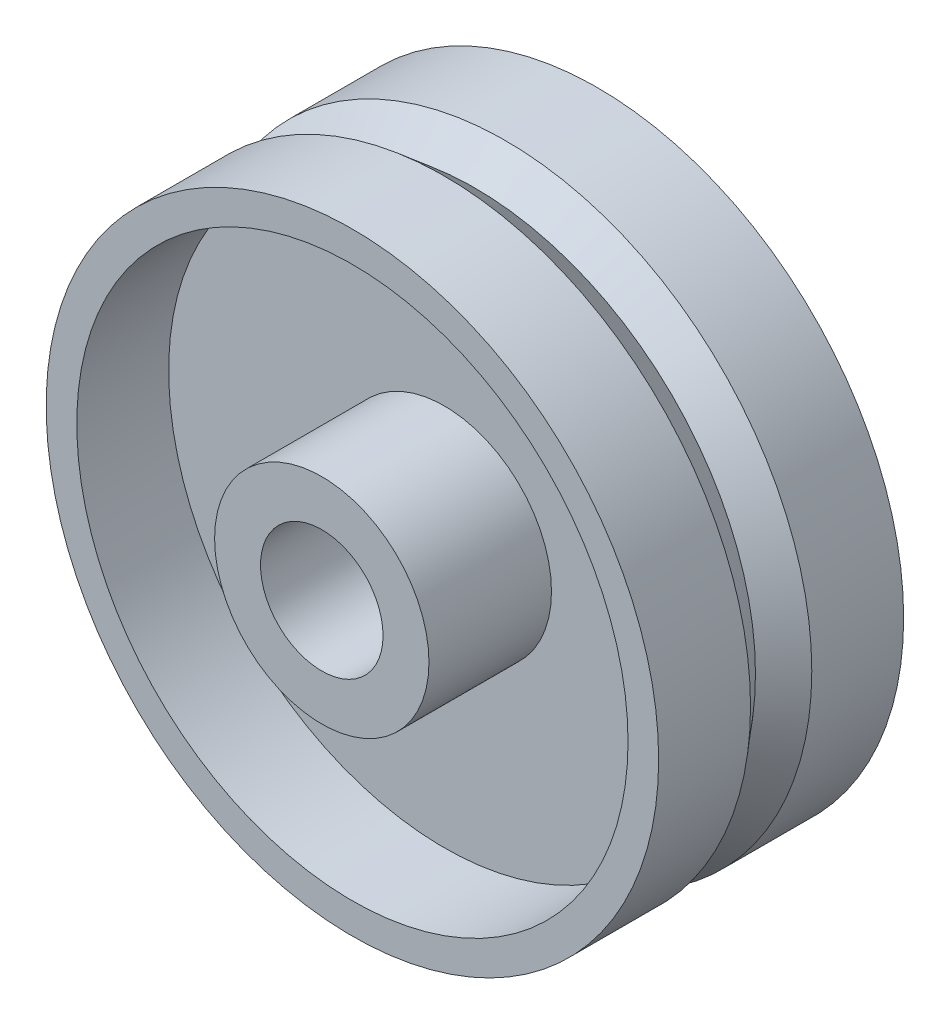
SolidWorks part; units mm, degrees
material "AISI 304"
ref_plane "Front Plane" through (0, 0, 0) normal (0, 0, 1) x (1, 0, 0)
ref_plane "Top Plane" through (0, 0, 0) normal (0, 1, 0) x (1, 0, 0)
ref_plane "Right Plane" through (0, 0, 0) normal (1, 0, 0) x (0, 0, -1)
sketch "Croquis1" plane through (0, 0, 0) normal (1, 0, 0) x (0, 0, -1)
  line L0 (0, 0) -> (65.4504, 0) construction
  line L1 (25, 10) -> (-25, 10)
  line L2 (-25, 10) -> (-25, 17.5)
  line L3 (-25, 17.5) -> (-5, 17.5)
  line L4 (-5, 17.5) -> (-5, 45)
  line L5 (-5, 45) -> (-20, 45)
  line L6 (-20, 45) -> (-20, 50)
  line L8 (20, 50) -> (20, 45)
  line L9 (20, 45) -> (5, 45)
  line L10 (5, 45) -> (5, 17.5)
  line L11 (5, 17.5) -> (25, 17.5)
  line L12 (25, 17.5) -> (25, 10)
  line L13 (-20, 50) -> (-5, 50)
  line L14 (5, 50) -> (20, 50)
  line L15 (0, 50) -> (0, 10) construction
  line L17 (-5, 50) -> (0, 45.8045)
  line L19 (0, 45.8045) -> (5, 50)
  point P6 (0, 10)
  dimension "D2" = 100
  dimension "D3" = 40
  dimension "D4" = 20
  dimension "D5" = 10
  dimension "D6" = 50
  dimension "D7" = 15
  dimension "D8" = 5
  dimension "D9" = 35
  dimension "D10" = 20
  dimension "D11" = 40
revolve "Revolución3" add sketch "Croquis1" angle 360 about L0
